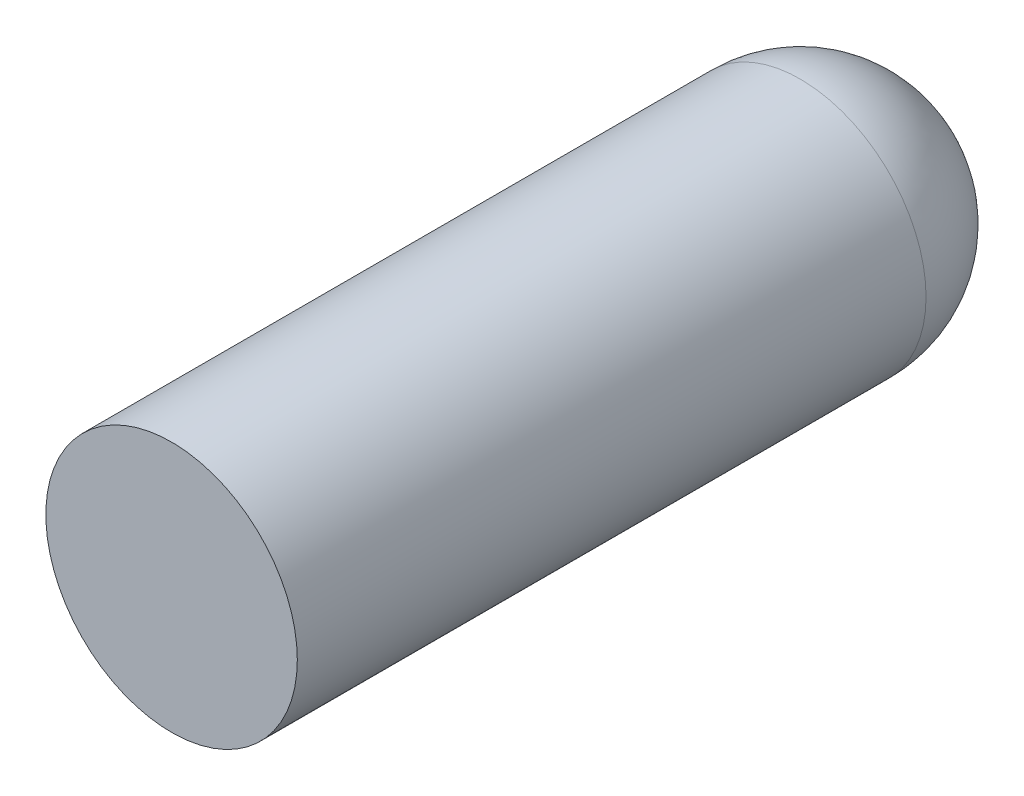
SolidWorks part; units mm, degrees
ref_plane "前视基准面" through (0, 0, 0) normal (0, 0, 1) x (1, 0, 0)
ref_plane "上视基准面" through (0, 0, 0) normal (0, 1, 0) x (1, 0, 0)
ref_plane "右视基准面" through (0, 0, 0) normal (1, 0, 0) x (0, 0, -1)
other "Configuration Table"
sketch "草图1" plane through (0, 0, 0) normal (0, 0, 1) x (1, 0, 0)
  circle A0 centre (0, 0) radius 10
  dimension "D1" = 20
extrude "凸台-拉伸1" add sketch "草图1" along normal blind 50
sketch "草图2" plane through (0, 0, 0) normal (0, 1, 0) x (1, 0, 0)
  line L1 (0, 10) -> (0, -10)
  arc A0 (0, -10) -> (0, 10) centre (0, 0) ccw
revolve "旋转1" add sketch "草图2" angle 360 about L1
